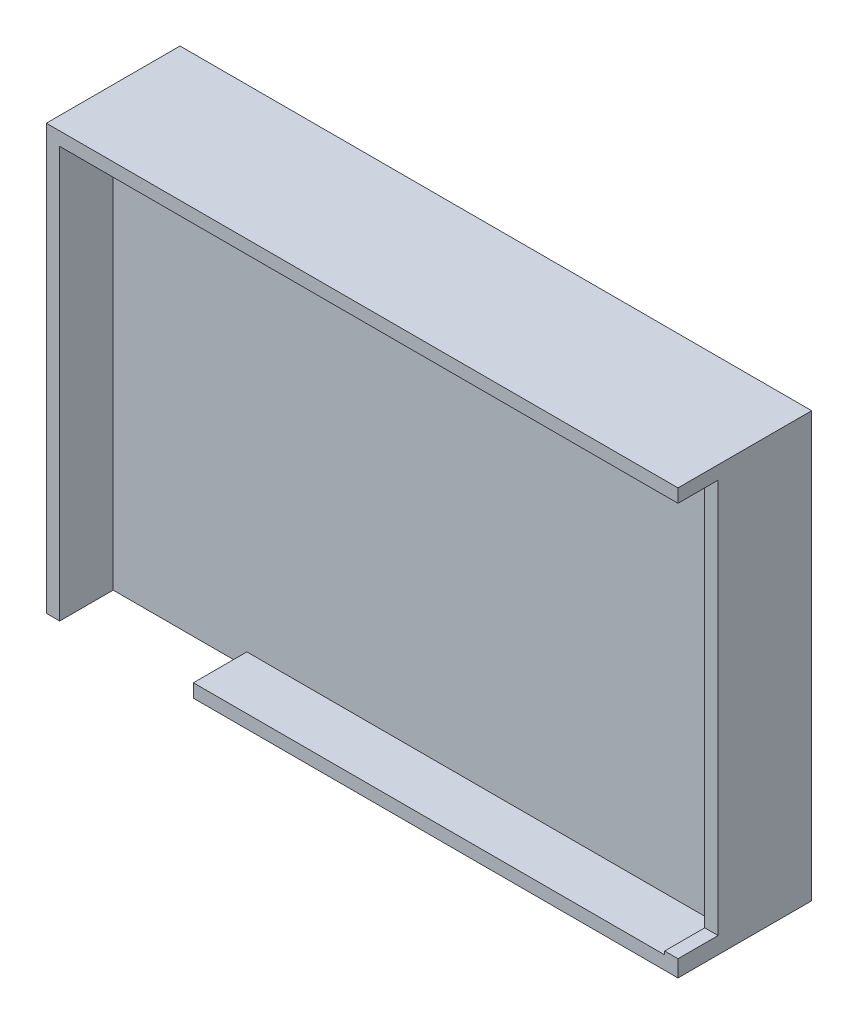
SolidWorks part; units mm, degrees
other "Markup1"
sketch "Sketch4" plane through (46, -30.5, -10) normal (0.7071, 0, -0.7071) x (-0.7071, 0, -0.7071)
ref_plane "Front Plane" through (0, 0, 0) normal (0, 0, 1) x (1, 0, 0)
ref_plane "Top Plane" through (0, 0, 0) normal (0, 1, 0) x (1, 0, 0)
ref_plane "Right Plane" through (0, 0, 0) normal (1, 0, 0) x (0, 0, -1)
sketch "Sketch1" plane through (0, 0, 0) normal (0, 0, 1) x (1, 0, 0)
  line L1 (-45.25, -29.75) -> (45.25, -29.75)
  line L2 (-45.25, -29.75) -> (-45.25, 29.75)
  line L3 (-45.25, 29.75) -> (45.25, 29.75)
  line L4 (45.25, -29.75) -> (45.25, 29.75)
  line L5 (-45.25, -29.75) -> (45.25, 29.75) construction
  line L6 (-45.25, 29.75) -> (45.25, -29.75) construction
  line L7 (47.25, -31.75) -> (-47.25, -31.75)
  line L8 (47.25, -31.75) -> (47.25, 31.75)
  line L9 (47.25, 31.75) -> (-47.25, 31.75)
  line L10 (-47.25, -31.75) -> (-47.25, 31.75)
  line L11 (47.25, -31.75) -> (-47.25, 31.75) construction
  line L12 (47.25, 31.75) -> (-47.25, -31.75) construction
  point P0 (0, 0)
  point P6 (0, 0)
  dimension "D1" = 90.5
  dimension "D2" = 59.5
  dimension "D3" = 63.5
  dimension "D4" = 94.5
extrude "Boss-Extrude1" add sketch "Sketch1" along normal blind 10
sketch "Sketch2" plane through (0, 0, 0) normal (0, 0, 1) x (1, 0, 0)
  line L1 (-47.25, -31.75) -> (47.25, -31.75)
  line L2 (-47.25, -31.75) -> (-47.25, 31.75)
  line L3 (-47.25, 31.75) -> (47.25, 31.75)
  line L4 (47.25, -31.75) -> (47.25, 31.75)
  line L5 (-47.25, -31.75) -> (47.25, 31.75) construction
  line L6 (-47.25, 31.75) -> (47.25, -31.75) construction
  point P0 (0, 0)
extrude "Boss-Extrude2" add sketch "Sketch2" along normal blind 2
sketch "Sketch3" plane through (0, 0, 0) normal (0, 0, -1) x (-1, 0, 0)
  line L1 (-47.25, -31.75) -> (47.25, -31.75)
  line L2 (-47.25, -31.75) -> (-47.25, 31.75)
  line L3 (-47.25, 31.75) -> (47.25, 31.75)
  line L4 (47.25, -31.75) -> (47.25, 31.75)
  line L5 (-47.25, -31.75) -> (47.25, 31.75) construction
  line L6 (-47.25, 31.75) -> (47.25, -31.75) construction
  line L8 (46, -1.65) -> (46, 1.65)
  line L10 (-47.25, -1.65) -> (-47.25, 1.65)
  line L11 (38, -1.65) -> (-38, -1.65)
  line L12 (38, -1.65) -> (38, 1.65)
  line L13 (38, 1.65) -> (-38, 1.65)
  line L14 (-38, -1.65) -> (-38, 1.65)
  line L15 (38, -1.65) -> (-38, 1.65) construction
  line L16 (38, 1.65) -> (-38, -1.65) construction
  point P0 (0, 0)
  point P7 (0, 0)
  point P13 (0, 0)
  dimension "D1" = 3.3
  dimension "D2" = 76
extrude "Boss-Extrude3" add sketch "Sketch3" along normal blind 10
sketch "Sketch5" plane through (0, 0, 10) normal (0, 0, 1) x (1, 0, 0)
  line L0 (-47.25, -31.75) -> (47.25, -31.75) construction
  line L1 (-45.25, -29.75) -> (-25.25, -29.75)
  line L2 (-45.25, -29.75) -> (-45.25, -31.75)
  line L3 (-45.25, -31.75) -> (-25.25, -31.75)
  line L4 (-25.25, -29.75) -> (-25.25, -31.75)
  dimension "D1" = 20
extrude "Cut-Extrude1" cut sketch "Sketch5" against normal up to surface (8 mm away) up to face at (0, 0, 2)
sketch "Sketch6" plane through (0, 0, 10) normal (0, 0, 1) x (1, 0, 0)
  line L0 (47.25, -31.75) -> (47.25, 31.75) construction
  line L1 (45.25, 29.75) -> (47.25, 29.75)
  line L2 (45.25, 29.75) -> (45.25, -29.25)
  line L3 (45.25, -29.25) -> (47.25, -29.25)
  line L4 (47.25, 29.75) -> (47.25, -29.25)
  dimension "D1" = 59
extrude "Cut-Extrude2" cut sketch "Sketch6" against normal blind 6
